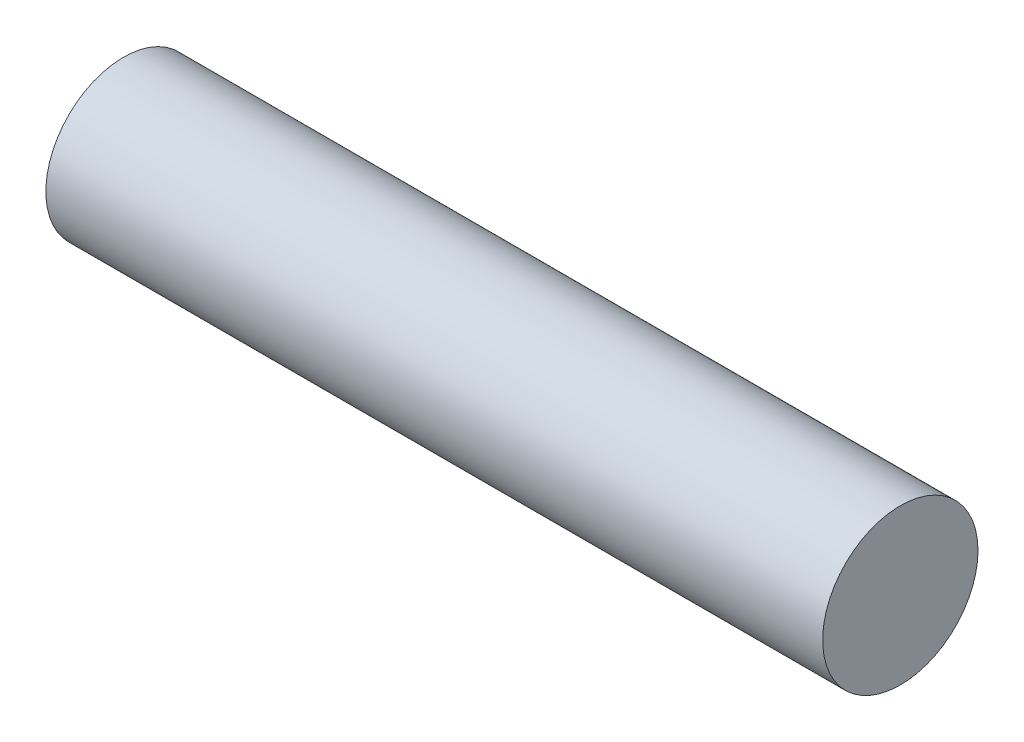
SolidWorks part; units mm, degrees
material "Commercialement pur CP-Ti UNS R50400 (SS)"
ref_plane "Plan de face" through (0, 0, 0) normal (0, 0, 1) x (1, 0, 0)
ref_plane "Plan de dessus" through (0, 0, 0) normal (0, 1, 0) x (1, 0, 0)
ref_plane "Plan de droite" through (0, 0, 0) normal (1, 0, 0) x (0, 0, -1)
sketch "Esquisse1" plane through (0, 0, 0) normal (1, 0, 0) x (0, 0, -1)
  circle A0 centre (0, 0) radius 15
  dimension "D1" = 30
extrude "Boss.-Extru.1" add sketch "Esquisse1" along normal blind 150
